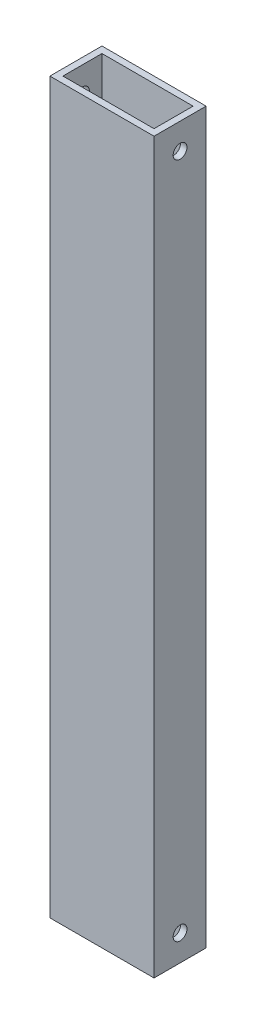
SolidWorks part; units mm, degrees
ref_plane "Front Plane" through (0, 0, 0) normal (0, 0, 1) x (1, 0, 0)
ref_plane "Top Plane" through (0, 0, 0) normal (0, 1, 0) x (1, 0, 0)
ref_plane "Right Plane" through (0, 0, 0) normal (1, 0, 0) x (0, 0, -1)
sketch "Sketch1" plane through (0, 0, 0) normal (0, 1, 0) x (1, 0, 0)
  line L0 (3.175, 3.175) -> (3.175, 22.225)
  line L1 (0, 0) -> (50.8, 0)
  line L2 (0, 0) -> (0, 25.4)
  line L3 (0, 25.4) -> (50.8, 25.4)
  line L4 (50.8, 0) -> (50.8, 25.4)
  line L5 (3.175, 22.225) -> (47.625, 22.225)
  line L6 (47.625, 3.175) -> (47.625, 22.225)
  line L7 (3.175, 3.175) -> (47.625, 3.175)
  dimension "D1" = 50.8
  dimension "D2" = 25.4
  dimension "D3" = 3.175
extrude "Boss-Extrude1" add sketch "Sketch1" along normal blind 355.6
sketch "Sketch2" plane through (50.8, 0, 0) normal (1, 0, 0) x (0, 0, -1)
  line L0 (25.4, 355.6) -> (25.4, 0) construction
  line L1 (13.97, 0) -> (-13.97, 0) construction
  circle A0 centre (12.7, 12.7) radius 3.3734
  dimension "D1" = 6.7469
  dimension "D2" = 12.7
  dimension "D3" = 12.7
extrude "Cut-Extrude1" cut sketch "Sketch2" against normal through all
ref_plane "Plane1" through (0, 177.8, 0) normal (0, 1, 0) x (1, 0, 0)
mirror "Mirror1" about plane through (0, 177.8, 0) normal (0, 1, 0) of "Cut-Extrude1"
